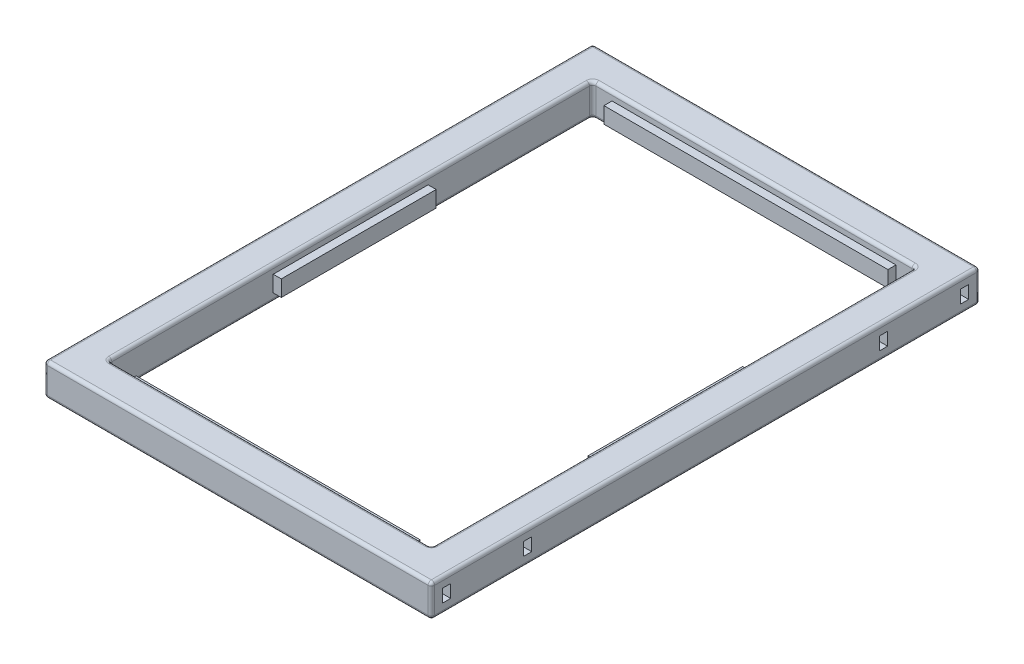
SolidWorks part; units mm, degrees
ref_plane "Front Plane" through (0, 0, 0) normal (0, 0, 1) x (1, 0, 0)
ref_plane "Top Plane" through (0, 0, 0) normal (0, 1, 0) x (1, 0, 0)
ref_plane "Right Plane" through (0, 0, 0) normal (1, 0, 0) x (0, 0, -1)
ref_plane "Plane1" through (0, 0, 0) normal (0, -1, 0) x (1, 0, 0)
sketch "Sketch1" plane through (0, 0, 0) normal (0, -1, 0) x (1, 0, 0)
  line L0 (114.3831, -82.1423) -> (114.3831, 257.8577)
  line L1 (114.3831, 257.8577) -> (-125.6169, 257.8577)
  line L2 (-125.6169, 257.8577) -> (-125.6169, -82.1423)
  line L3 (-125.6169, -82.1423) -> (114.3831, -82.1423)
extrude "Boss-Extrude1" add sketch "Sketch1" against normal blind 20
sketch "Sketch2" plane through (0, 20, 0) normal (0, 1, 0) x (-1, 0, 0)
  line L0 (-94.3831, 237.8577) -> (-94.3831, -62.1423)
  line L1 (-94.3831, -62.1423) -> (105.6169, -62.1423)
  line L2 (105.6169, -62.1423) -> (105.6169, 237.8577)
  line L3 (105.6169, 237.8577) -> (-94.3831, 237.8577)
extrude "Cut-Extrude1" cut sketch "Sketch2" against normal through all
sketch "Sketch3" plane through (-105.6169, 0, 0) normal (1, 0, 0) x (0, 0, -1)
  line L0 (-135.8577, 15) -> (-39.8577, 15)
  line L1 (-39.8577, 15) -> (-39.8577, 5)
  line L2 (-39.8577, 5) -> (-135.8577, 5)
  line L3 (-135.8577, 5) -> (-135.8577, 15)
extrude "Boss-Extrude2" add sketch "Sketch3" along normal blind 5
sketch "Sketch4" plane through (94.3831, 0, 0) normal (-1, 0, 0) x (0, 0, 1)
  line L0 (39.8577, 15) -> (135.8577, 15)
  line L1 (135.8577, 15) -> (135.8577, 5)
  line L2 (135.8577, 5) -> (39.8577, 5)
  line L3 (39.8577, 5) -> (39.8577, 15)
extrude "Boss-Extrude3" add sketch "Sketch4" along normal blind 5
sketch "Sketch5" plane through (0, 0, 237.8577) normal (0, 0, -1) x (-1, 0, 0)
  line L0 (-82.3831, 15) -> (93.6169, 15)
  line L1 (93.6169, 15) -> (93.6169, 5)
  line L2 (93.6169, 5) -> (-82.3831, 5)
  line L3 (-82.3831, 5) -> (-82.3831, 15)
extrude "Boss-Extrude4" add sketch "Sketch5" along normal blind 5
sketch "Sketch6" plane through (0, 0, -62.1423) normal (0, 0, 1) x (1, 0, 0)
  line L0 (82.3831, 15) -> (82.3831, 5)
  line L1 (82.3831, 5) -> (-93.6169, 5)
  line L2 (-93.6169, 5) -> (-93.6169, 15)
  line L3 (-93.6169, 15) -> (82.3831, 15)
extrude "Boss-Extrude5" add sketch "Sketch6" along normal blind 5
sketch "Sketch7" plane through (114.3831, 0, 0) normal (1, 0, 0) x (0, 0, -1)
  line L0 (-245.8577, 14) -> (-250.8577, 14)
  line L1 (-250.8577, 14) -> (-250.8577, 6)
  line L2 (-250.8577, 6) -> (-245.8577, 6)
  line L3 (-245.8577, 6) -> (-245.8577, 14)
extrude "Cut-Extrude2" cut sketch "Sketch7" against normal blind 10
sketch "Sketch8" plane through (114.3831, 0, 0) normal (1, 0, 0) x (0, 0, -1)
  line L0 (-195.6577, 14) -> (-200.6577, 14)
  line L1 (-200.6577, 14) -> (-200.6577, 6)
  line L2 (-200.6577, 6) -> (-195.6577, 6)
  line L3 (-195.6577, 6) -> (-195.6577, 14)
extrude "Cut-Extrude3" cut sketch "Sketch8" against normal blind 10
sketch "Sketch9" plane through (114.3831, 0, 0) normal (1, 0, 0) x (0, 0, -1)
  line L0 (19.9423, 6) -> (24.9423, 6)
  line L1 (24.9423, 6) -> (24.9423, 14)
  line L2 (24.9423, 14) -> (19.9423, 14)
  line L3 (19.9423, 14) -> (19.9423, 6)
extrude "Cut-Extrude4" cut sketch "Sketch9" against normal blind 10
sketch "Sketch10" plane through (114.3831, 0, 0) normal (1, 0, 0) x (0, 0, -1)
  line L0 (70.1423, 6) -> (75.1423, 6)
  line L1 (75.1423, 6) -> (75.1423, 14)
  line L2 (75.1423, 14) -> (70.1423, 14)
  line L3 (70.1423, 14) -> (70.1423, 6)
extrude "Cut-Extrude5" cut sketch "Sketch10" against normal blind 10
sketch "Sketch11" plane through (-125.6169, 0, 0) normal (-1, 0, 0) x (0, 0, 1)
  line L0 (245.8577, 6) -> (250.8577, 6)
  line L1 (250.8577, 6) -> (250.8577, 14)
  line L2 (250.8577, 14) -> (245.8577, 14)
  line L3 (245.8577, 14) -> (245.8577, 6)
extrude "Cut-Extrude6" cut sketch "Sketch11" against normal blind 10
sketch "Sketch12" plane through (-125.6169, 0, 0) normal (-1, 0, 0) x (0, 0, 1)
  line L0 (195.6577, 6) -> (200.6577, 6)
  line L1 (200.6577, 6) -> (200.6577, 14)
  line L2 (200.6577, 14) -> (195.6577, 14)
  line L3 (195.6577, 14) -> (195.6577, 6)
extrude "Cut-Extrude7" cut sketch "Sketch12" against normal blind 10
sketch "Sketch13" plane through (-125.6169, 0, 0) normal (-1, 0, 0) x (0, 0, 1)
  line L0 (-19.9423, 14) -> (-24.9423, 14)
  line L1 (-24.9423, 14) -> (-24.9423, 6)
  line L2 (-24.9423, 6) -> (-19.9423, 6)
  line L3 (-19.9423, 6) -> (-19.9423, 14)
extrude "Cut-Extrude8" cut sketch "Sketch13" against normal blind 10
sketch "Sketch14" plane through (-125.6169, 0, 0) normal (-1, 0, 0) x (0, 0, 1)
  line L0 (-70.1423, 14) -> (-75.1423, 14)
  line L1 (-75.1423, 14) -> (-75.1423, 6)
  line L2 (-75.1423, 6) -> (-70.1423, 6)
  line L3 (-70.1423, 6) -> (-70.1423, 14)
extrude "Cut-Extrude9" cut sketch "Sketch14" against normal blind 10
fillet "Fillet1" radius 2 24 edges at (-5.6169, 20, -62.1423) (-105.6169, 20, 87.8577) (94.3831, 10, -62.1423) (-105.6169, 10, -62.1423) (94.3831, 20, 87.8577) (94.3831, 10, 237.8577) (-105.6169, 10, 237.8577) (-5.6169, 20, 237.8577) (-5.6169, 20, -82.1423) (-125.6169, 10, -82.1423) (114.3831, 10, -82.1423) (-125.6169, 20, 87.8577) (114.3831, 20, 87.8577) (-5.6169, 20, 257.8577) (-5.6169, 0, -82.1423) (-125.6169, 0, 87.8577) (114.3831, 0, 87.8577) (-125.6169, 10, 257.8577) (114.3831, 10, 257.8577) (-5.6169, 0, 257.8577) (-105.6169, 0, 87.8577) (-5.6169, 0, -62.1423) (-5.6169, 0, 237.8577) (94.3831, 0, 87.8577)
